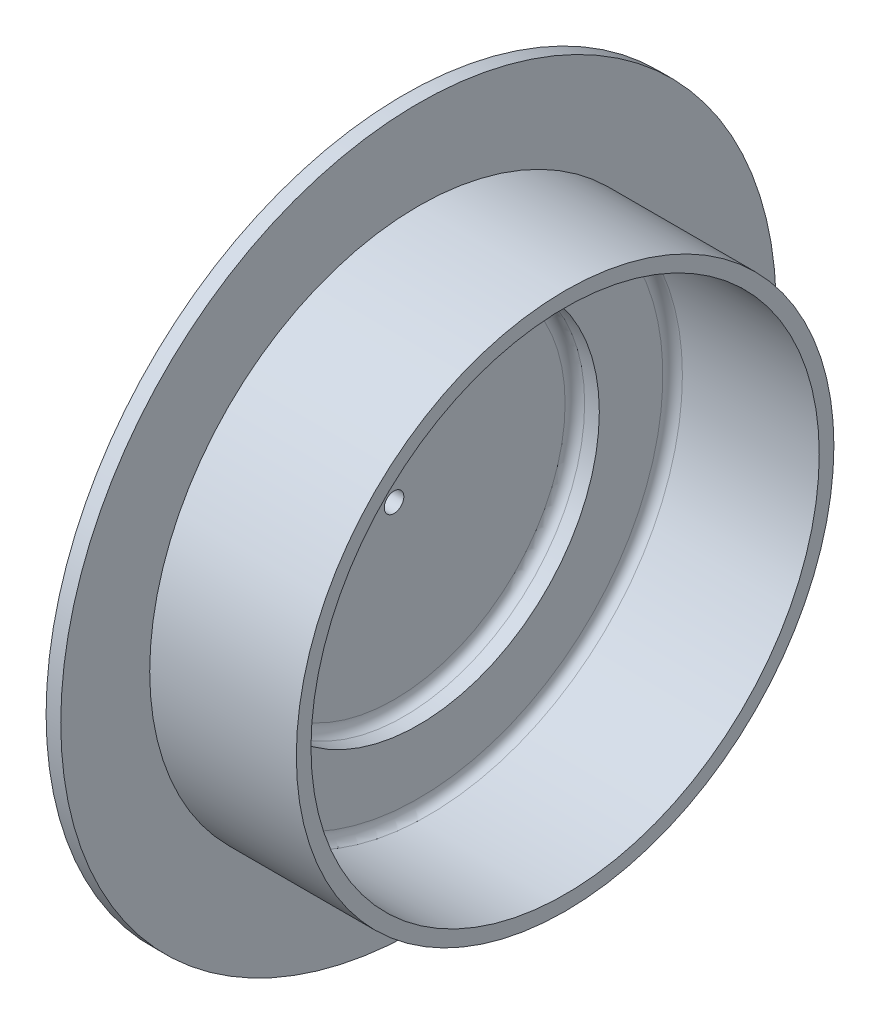
SolidWorks part; units mm, degrees
ref_plane "Front Plane" through (0, 0, 0) normal (0, 0, 1) x (1, 0, 0)
ref_plane "Top Plane" through (0, 0, 0) normal (0, 1, 0) x (1, 0, 0)
ref_plane "Right Plane" through (0, 0, 0) normal (1, 0, 0) x (0, 0, -1)
sketch "Sketch1" plane through (0, 0, 0) normal (0, 0, 1) x (1, 0, 0)
  line L0 (0, 40) -> (0, 37)
  line L1 (0, 37) -> (8, 37)
  line L2 (10, 35) -> (10, 2)
  line L3 (10, 2) -> (13, 2)
  line L4 (13, 2) -> (13, 35)
  line L5 (15, 37) -> (18, 37)
  line L6 (18, 37) -> (18, 50)
  line L7 (20, 52) -> (48, 52)
  line L8 (48, 52) -> (48, 55)
  line L9 (48, 55) -> (18, 55)
  line L10 (15, 52) -> (15, 40)
  line L11 (15, 40) -> (0, 40)
  line L12 (0, 0) -> (13, 0) construction
  line L15 (15, 52) -> (15, 73.2)
  line L16 (15, 73.2) -> (18, 73.2)
  line L17 (18, 55) -> (18, 73.2)
  arc A0 (18, 50) -> (20, 52) centre (20, 50) cw
  arc A1 (13, 35) -> (15, 37) centre (15, 35) cw
  arc A2 (10, 35) -> (8, 37) centre (8, 35) ccw
  point P3 (16.5, 37)
  point P14 (0, 38.5)
  dimension "D12" = 2
  dimension "D1" = 2
  dimension "D2" = 3
  dimension "D3" = 3
  dimension "D4" = 3
  dimension "D5" = 3
  dimension "D6" = 40
  dimension "D7" = 3
  dimension "D8" = 10
  dimension "D9" = 73.2
  dimension "D10" = 55
  dimension "D11" = 15
  dimension "D13" = 30
  dimension "D14" = 3
revolve "Revolve1" add sketch "Sketch1" angle 360 about L12
